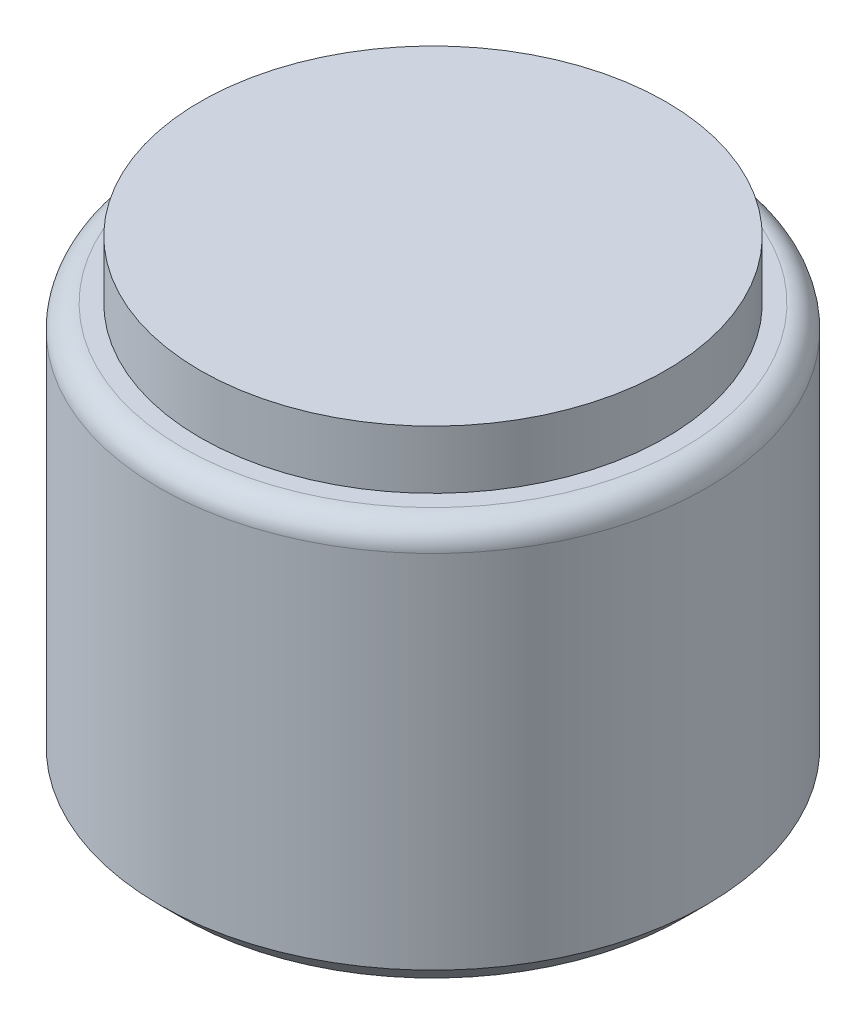
SolidWorks part; units mm, degrees
ref_plane "Front" through (0, 0, 0) normal (0, 0, 1) x (1, 0, 0)
ref_plane "Top" through (0, 0, 0) normal (0, 1, 0) x (1, 0, 0)
ref_plane "Right" through (0, 0, 0) normal (1, 0, 0) x (0, 0, -1)
sketch "草图1" plane through (0, 0, 0) normal (0, 0, 1) x (1, 0, 0)
  line L0 (0, 0) -> (100, 0)
  line L1 (100, 0) -> (100, -25)
  line L2 (100, -25) -> (117.5, -25)
  line L3 (117.5, -25) -> (117.5, -200)
  line L4 (117.5, -200) -> (67.5, -200)
  line L5 (67.5, -200) -> (67.5, -165)
  line L6 (67.5, -165) -> (0, -165)
  line L7 (0, -165) -> (0, 0)
  line L8 (0, 0) -> (0, 41.4616) construction
  point P9 (33.75, -165)
  dimension "D1" = 200
  dimension "D2" = 25
  dimension "D3" = 235
  dimension "D4" = 200
  dimension "D5" = 35
  dimension "D6" = 135
revolve "旋转1" add sketch "草图1" angle 360 about L8
hole_wizard "M16 螺纹孔1" positions "草图2" profile "草图3" tap size "M16" standard "ISO"
sketch "草图2" plane through (0, -165, 0) normal (0, -1, 0) x (-1, 0, 0)
  point P0 (0, 0)
sketch "草图3" plane through (0, -165, 0) normal (1, 0, 0) x (0, 0, -1)
  line L0 (0, 0) -> (0, 42.206)
  line L1 (0, 42.206) -> (7, 38)
  line L2 (7, 38) -> (7, 0)
  line L5 (7, 0) -> (0, 0)
  line L10 (0, 42.206) -> (-7, 38) construction
  line L11 (0, -6.35) -> (0, 107.95) construction
  dimension "螺纹孔钻头直径" = 14
  dimension "螺纹孔钻头深度" = 38
  dimension "导头角度" = 118
cosmetic thread "孔螺蚊线1" parameters "D1"=32, "D2"=16
chamfer "倒角1" distance 10 angle 45 1 edges at (0, -200, -117.5)
fillet "圆角1" radius 10 1 edges at (0, -25, -117.5)
